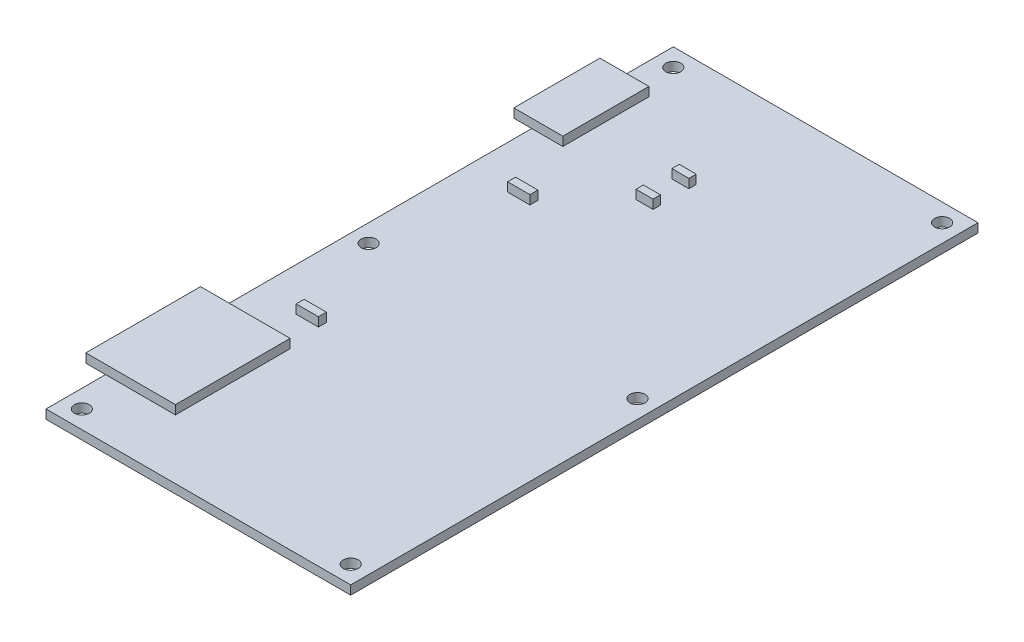
SolidWorks part; units mm, degrees
ref_plane "Front Plane" through (0, 0, 0) normal (0, 0, 1) x (1, 0, 0)
ref_plane "Top Plane" through (0, 0, 0) normal (0, 1, 0) x (1, 0, 0)
ref_plane "Right Plane" through (0, 0, 0) normal (1, 0, 0) x (0, 0, -1)
sketch "Sketch1" plane through (0, 0, 0) normal (0, 1, 0) x (1, 0, 0)
  line L1 (0, 0) -> (107.95, 0)
  line L2 (0, 0) -> (0, 222.25)
  line L3 (0, 222.25) -> (107.95, 222.25)
  line L4 (107.95, 0) -> (107.95, 222.25)
  dimension "D1" = 222.25
  dimension "D2" = 107.95
extrude "Boss-Extrude1" add sketch "Sketch1" along normal blind 3.175
sketch "Sketch3" plane through (0, 3.175, 0) normal (0, 1, 0) x (1, 0, 0)
  line L0 (107.95, 222.25) -> (0, 222.25) construction
  line L1 (11.0236, 202.5904) -> (-6.35, 202.5904)
  line L2 (11.0236, 202.5904) -> (11.0236, 172.085)
  line L3 (11.0236, 172.085) -> (-6.35, 172.085)
  line L4 (-6.35, 202.5904) -> (-6.35, 172.085)
  line L5 (0, 222.25) -> (0, 0) construction
  line L6 (0, 0) -> (107.95, 0) construction
  line L7 (15.24, 151.13) -> (23.1394, 151.13)
  line L8 (15.24, 151.13) -> (15.24, 148.3106)
  line L9 (15.24, 148.3106) -> (23.1394, 148.3106)
  line L10 (23.1394, 151.13) -> (23.1394, 148.3106)
  line L11 (15.24, 76.2) -> (23.1394, 76.2)
  line L12 (15.24, 76.2) -> (15.24, 73.3806)
  line L13 (15.24, 73.3806) -> (23.1394, 73.3806)
  line L14 (23.1394, 76.2) -> (23.1394, 73.3806)
  line L15 (16.383, 54.3814) -> (21.971, 54.3814)
  line L16 (16.383, 54.3814) -> (16.383, 22.098)
  line L17 (16.383, 22.098) -> (21.971, 22.098)
  line L18 (21.971, 54.3814) -> (21.971, 22.098)
  line L20 (40.2844, 184.0738) -> (46.3042, 184.0738)
  line L21 (40.2844, 184.0738) -> (40.2844, 181.4576)
  line L22 (40.2844, 181.4576) -> (46.3042, 181.4576)
  line L23 (46.3042, 184.0738) -> (46.3042, 181.4576)
  line L24 (40.2844, 171.3738) -> (46.3042, 171.3738)
  line L25 (40.2844, 171.3738) -> (40.2844, 168.7576)
  line L26 (40.2844, 168.7576) -> (46.3042, 168.7576)
  line L27 (46.3042, 171.3738) -> (46.3042, 168.7576)
  dimension "D1" = 19.6596
  dimension "D2" = 50.165
  dimension "D3" = 11.0236
  dimension "D4" = 6.35
  dimension "D5" = 7.8994
  dimension "D6" = 7.8994
  dimension "D7" = 2.8194
  dimension "D8" = 2.8194
  dimension "D9" = 77.7494
  dimension "D10" = 15.24
  dimension "D11" = 71.12
  dimension "D12" = 15.24
  dimension "D13" = 5.588
  dimension "D14" = 32.2834
  dimension "D15" = 22.098
  dimension "D16" = 16.383
  dimension "D17" = 40.2844
  dimension "D18" = 40.2844
  dimension "D19" = 6.0198
  dimension "D20" = 6.0198
  dimension "D21" = 2.6162
  dimension "D22" = 2.6162
  dimension "D23" = 15.3162
  dimension "D24" = 38.1762
extrude "Boss-Extrude2" add sketch "Sketch3" along normal blind 3.175
hole_wizard "#4 (0.209) Diameter Hole1" positions "Sketch5" profile "Sketch6" hole size "#4" standard "ANSI Inch" end condition through all
sketch "Sketch5" plane through (0, 3.175, 0) normal (0, 1, 0) x (1, 0, 0)
  line L0 (107.95, 222.25) -> (0, 222.25) construction
  line L1 (0, 222.25) -> (0, 202.5904) construction
  line L2 (107.95, 0) -> (107.95, 222.25) construction
  line L3 (0, 0) -> (107.95, 0) construction
  line L4 (0, 172.085) -> (0, 0) construction
  point P0 (101.6, 215.9)
  point P2 (101.6, 6.35)
  point P4 (6.35, 6.35)
  point P6 (6.35, 215.9)
  point P19 (6.35, 107.95)
  point P21 (101.6, 107.95)
  dimension "D1" = 6.35
  dimension "D2" = 6.35
  dimension "D3" = 6.35
  dimension "D4" = 6.35
  dimension "D5" = 6.35
  dimension "D6" = 6.35
  dimension "D7" = 6.35
  dimension "D8" = 6.35
  dimension "D9" = 6.35
  dimension "D10" = 6.35
  dimension "D11" = 107.95
  dimension "D12" = 107.95
sketch "Sketch6" plane through (101.6, 3.175, -215.9) normal (1, 0, 0) x (0, 0, 1)
  line L0 (0, 0) -> (0, 3.175)
  line L1 (0, 3.175) -> (2.6543, 3.175)
  line L2 (2.6543, 3.175) -> (2.6543, 0)
  line L5 (2.6543, 0) -> (0, 0)
  line L11 (0, -6.35) -> (0, 107.95) construction
  dimension "Thru Hole Dia." = 5.3086
  dimension "Thru Hole Depth" = 3.175
sketch "Sketch7" plane through (0, 6.35, 0) normal (0, 1, 0) x (1, 0, 0)
  line L0 (21.971, 22.098) -> (21.971, 54.3814) construction
  line L1 (-3.81, 58.5597) -> (27.94, 58.5597)
  line L2 (-3.81, 58.5597) -> (-3.81, 17.9197)
  line L3 (-3.81, 17.9197) -> (27.94, 17.9197)
  line L4 (27.94, 58.5597) -> (27.94, 17.9197)
  line L8 (0, 172.085) -> (0, 0) construction
  point P4 (21.971, 38.2397)
  dimension "D1" = 27.94
  dimension "D2" = 40.64
  dimension "D3" = 20.32
  dimension "D4" = 31.75
extrude "Boss-Extrude3" add sketch "Sketch7" along normal blind 3.175
